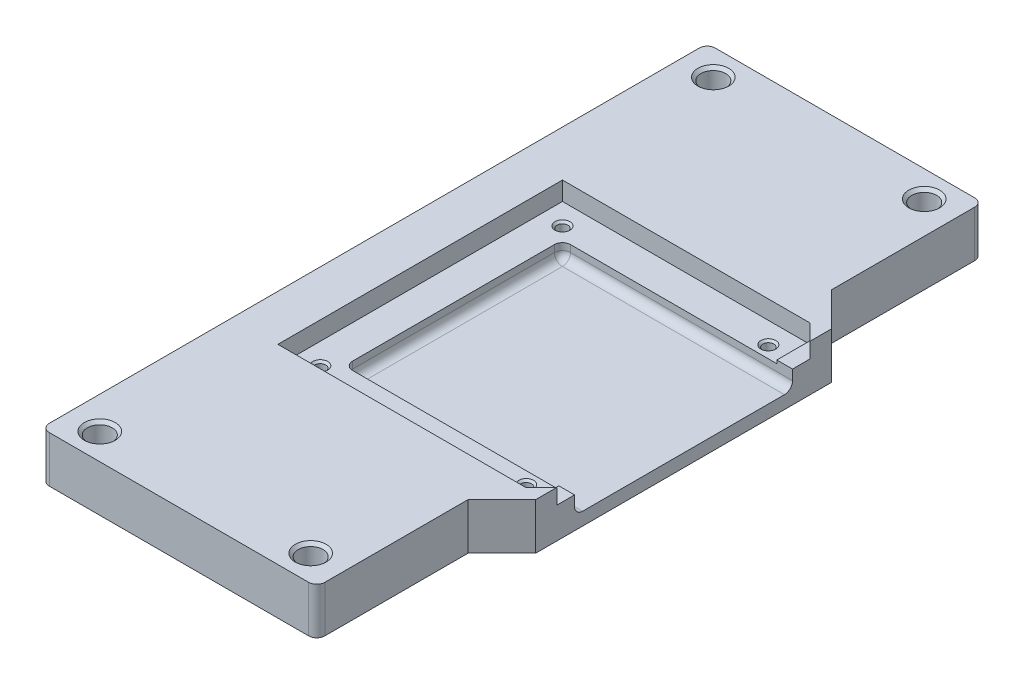
SolidWorks part; units mm, degrees
ref_plane "Front Plane" through (0, 0, 0) normal (0, 0, 1) x (1, 0, 0)
ref_plane "Top Plane" through (0, 0, 0) normal (0, 1, 0) x (1, 0, 0)
ref_plane "Right Plane" through (0, 0, 0) normal (1, 0, 0) x (0, 0, -1)
sketch "Sketch1" plane through (0, 0, 0) normal (0, 1, 0) x (1, 0, 0)
  line L0 (0, -67.5) -> (0, 67.5) construction
  line L1 (34.125, 67.5) -> (-34.125, 67.5) construction
  line L2 (-34.125, 67.5) -> (-34.125, -67.5)
  line L3 (-34.125, 0) -> (34.125, 0) construction
  line L4 (-34.125, 67.5) -> (-34.125, 80.5)
  line L5 (-32.125, 82.5) -> (32.125, 82.5)
  line L6 (0, 82.5) -> (0, 67.5) construction
  line L7 (34.125, 67.5) -> (34.125, 80.5)
  line L8 (34.125, 67.5) -> (34.125, -67.5)
  line L9 (0, -82.5) -> (0, -67.5) construction
  line L10 (34.125, -67.5) -> (-34.125, -67.5) construction
  line L11 (34.125, -67.5) -> (34.125, -80.5)
  line L12 (-32.125, -82.5) -> (32.125, -82.5)
  line L13 (-34.125, -67.5) -> (-34.125, -80.5)
  line L14 (-34.125, 70.5) -> (34.125, 70.5) construction
  circle A1 centre (-26.125, 76) radius 3.075 construction
  circle A2 centre (26.125, 76) radius 3.075 construction
  circle A5 centre (26.125, -76) radius 3.075 construction
  circle A6 centre (-26.125, -76) radius 3.075 construction
  arc A8 (-32.125, -82.5) -> (-34.125, -80.5) centre (-32.125, -80.5) cw
  arc A9 (34.125, -80.5) -> (32.125, -82.5) centre (32.125, -80.5) cw
  arc A10 (34.125, 80.5) -> (32.125, 82.5) centre (32.125, 80.5) ccw
  arc A11 (-34.125, 80.5) -> (-32.125, 82.5) centre (-32.125, 80.5) cw
  point P24 (0, 0)
  point P36 (-34.125, -82.5)
  point P39 (34.125, -82.5)
  point P42 (34.125, 82.5)
  point P45 (-34.125, 82.5)
  dimension "D10" = 2
  dimension "D3" = 6.15
  dimension "D1" = 34.125
  dimension "D2" = 67.5
  dimension "D4" = 6.5
  dimension "D6" = 8
  dimension "D7" = 8.5
  dimension "D8" = 12
  dimension "D9" = 3
  dimension "D11" = 82.5
extrude "Boss-Extrude1" add sketch "Sketch1" along normal blind 11.5
sketch "Sketch3" plane through (0, 11.5, 0) normal (0, 1, 0) x (1, 0, 0)
  line L0 (0, 0) -> (-34.125, 0) construction
  line L1 (-34.125, 80.5) -> (-34.125, -80.5) construction
  line L2 (0, 0) -> (0, 82.5) construction
  line L3 (32.125, 82.5) -> (-32.125, 82.5) construction
  line L4 (3.96, -16.3) -> (3.96, 16.3)
  line L5 (-2.46, -17.8) -> (2.46, -17.8)
  line L6 (-3.96, 16.3) -> (-3.96, -16.3)
  line L7 (2.46, 17.8) -> (-2.46, 17.8)
  line L8 (0, 17.8) -> (0, -17.8) construction
  line L9 (13.25, 0) -> (0, 0) construction
  line L10 (16.15, 10.025) -> (10.35, 10.025)
  line L11 (16.15, 10.025) -> (16.15, -10.025)
  line L12 (16.15, -10.025) -> (10.35, -10.025)
  line L13 (10.35, 10.025) -> (10.35, -10.025)
  line L14 (16.15, 10.025) -> (10.35, -10.025) construction
  line L15 (16.15, -10.025) -> (10.35, 10.025) construction
  line L16 (13.25, 0) -> (13.25, 10.025) construction
  line L17 (-16.15, 10.025) -> (-16.15, -10.025)
  line L18 (-16.15, -10.025) -> (-10.35, -10.025)
  line L23 (-16.15, 10.025) -> (-10.35, 10.025)
  line L24 (-10.35, 10.025) -> (-10.35, -10.025)
  arc A0 (-2.46, 17.8) -> (-3.96, 16.3) centre (-2.46, 16.3) ccw
  arc A1 (3.96, 16.3) -> (2.46, 17.8) centre (2.46, 16.3) ccw
  arc A2 (2.46, -17.8) -> (3.96, -16.3) centre (2.46, -16.3) ccw
  arc A3 (-3.96, -16.3) -> (-2.46, -17.8) centre (-2.46, -16.3) ccw
  point P9 (0, 0)
  point P23 (0, 0)
  dimension "D2" = 1.5
  dimension "D1" = 35.6
  dimension "D3" = 7.92
  dimension "D4" = 20.05
  dimension "D5" = 5.8
  dimension "D6" = 13.25
sketch "Sketch4" plane through (0, 11.5, 0) normal (0, 1, 0) x (1, 0, 0)
  circle A0 centre (-26.125, -76) radius 3.075 construction
  circle A1 centre (26.125, -76) radius 3.075 construction
  circle A2 centre (26.125, 76) radius 3.075 construction
  circle A5 centre (-26.125, 76) radius 3.075 construction
  circle A8 centre (-26.125, -76) radius 3.075
  circle A9 centre (26.125, -76) radius 3.075
  circle A10 centre (26.125, 76) radius 3.075
  circle A13 centre (-26.125, 76) radius 3.075
extrude "Cut-Extrude1" cut sketch "Sketch4" against normal blind 6
sketch "Sketch27" plane through (0, 11.5, 0) normal (0, 1, 0) x (1, 0, 0)
  line L0 (38.5, 35) -> (-22.5, 35) construction
  line L1 (34.125, 45) -> (42.5, 36.625)
  line L2 (-22.5, 35) -> (-22.5, -35) construction
  line L3 (-22.5, 0) -> (0, 0) construction
  line L4 (38.5, -35) -> (38.5, 35) construction
  line L5 (38.5, -35) -> (-22.5, -35) construction
  line L7 (0, 0) -> (38.5, 0) construction
  line L8 (34.125, -80.5) -> (34.125, 80.5) construction
  line L9 (42.5, 36.625) -> (42.5, -36.625)
  line L10 (42.5, 0) -> (38.5, 0) construction
  line L11 (34.125, 45) -> (34.125, -45)
  line L12 (34.125, 0) -> (42.5, 0) construction
  line L13 (34.125, -45) -> (42.5, -36.625)
  circle A0 centre (-17.5, 30) radius 1.6 construction
  circle A1 centre (33.5, 30) radius 1.6 construction
  circle A2 centre (33.5, -30) radius 1.6 construction
  circle A3 centre (-17.5, -30) radius 1.6 construction
  dimension "D8" = 3.2
  dimension "D1" = 22.5
  dimension "D2" = 61
  dimension "D3" = 35
  dimension "D4" = 5
  dimension "D5" = 5
  dimension "D6" = 5
  dimension "D7" = 5
  dimension "D9" = 45
  dimension "D10" = 4
  dimension "D11" = 10
extrude "Boss-Extrude3" add sketch "Sketch27" against normal up to surface (11.5 mm away) up to face at (0, 0, 0)
sketch "Sketch21" plane through (0, 11.5, 0) normal (0, 1, 0) x (1, 0, 0)
  line L0 (38.5, 35) -> (-22.5, 35) construction
  line L1 (38.5, 35) -> (42.5, 31) construction
  line L2 (-22.5, 35) -> (-22.5, -35) construction
  line L3 (-22.5, 0) -> (0, 0) construction
  line L5 (38.5, -35) -> (38.5, 35) construction
  line L6 (38.5, -35) -> (-22.5, -35) construction
  line L7 (42.5, 31) -> (42.5, 31.3536) construction
  line L10 (0, 0) -> (38.5, 0) construction
  line L11 (42.5, 31.3536) -> (42.5, -31.3536)
  line L14 (38.6036, 35.25) -> (42.5, 31.3536)
  line L15 (38.6036, 35.25) -> (-22.75, 35.25)
  line L16 (-22.75, 35.25) -> (-22.75, -35.25)
  line L17 (38.6036, -35.25) -> (-22.75, -35.25)
  line L22 (41.1909, -32.6626) -> (40.4837, -33.8199) construction
  line L23 (42.5, 31.3536) -> (43.8534, 32.707) construction
  line L24 (42.5, -31) -> (40.697, -33.9503) construction
  line L25 (42.5, 31) -> (44.0302, 32.5302) construction
  line L26 (38.6036, -35.25) -> (41.1909, -32.6626) construction
  line L27 (38.5, -35) -> (42.5, -31) construction
  line L29 (42.5, 0) -> (38.5, 0) construction
  line L30 (42.5, -36.625) -> (42.5, 36.625) construction
  line L31 (38.6036, -35.25) -> (42.5, -31.3536)
  circle A0 centre (-17.5, 30) radius 1.6 construction
  circle A1 centre (33.5, 30) radius 1.6 construction
  circle A2 centre (33.5, -30) radius 1.6 construction
  circle A3 centre (-17.5, -30) radius 1.6 construction
  point P2 (-123.1318, 54.1866)
  point P19 (42.5, 0)
  dimension "D8" = 3.2
  dimension "D1" = 22.5
  dimension "D2" = 61
  dimension "D3" = 35
  dimension "D4" = 5
  dimension "D5" = 5
  dimension "D6" = 5
  dimension "D7" = 5
  dimension "D9" = 45
  dimension "D10" = 4
  dimension "D11" = 0.25
extrude "Cut-Extrude6" cut sketch "Sketch21" against normal blind 4.6
sketch "Sketch24" plane through (0, 6.9, 0) normal (0, 1, 0) x (1, 0, 0)
  line L0 (42.5, 27) -> (-14.5, 27)
  line L1 (42.5, -31.3536) -> (42.5, 31.3536) construction
  line L2 (-14.5, 27) -> (-14.5, -27)
  line L3 (-14.5, -27) -> (42.5, -27)
  line L4 (42.5, -27) -> (42.5, 27)
  line L8 (38.5, 35) -> (-22.5, 35) construction
  line L10 (-22.5, 35) -> (-22.5, -35) construction
  line L11 (38.5, -35) -> (-22.5, -35) construction
  point P2 (0, 0)
  point P3 (42.5, -27)
  dimension "D1" = 8
  dimension "D2" = 8
  dimension "D3" = 8
extrude "Cut-Extrude3" cut sketch "Sketch24" against normal blind 3.7 and the other way through all
sketch "Sketch25" plane through (0, 6.9, 0) normal (0, 1, 0) x (1, 0, 0)
  circle A0 centre (33.5, 30) radius 1.35
  circle A1 centre (-17.5, 30) radius 1.35
  circle A2 centre (33.5, -30) radius 1.35
  circle A3 centre (-17.5, -30) radius 1.35
  dimension "D1" = 2.7
extrude "Cut-Extrude4" cut sketch "Sketch25" against normal blind 5
chamfer "Chamfer4" distance 0.5 angle 45 4 edges at (-17.5, 6.9, 31.35) (33.5, 6.9, 31.35) (33.5, 6.9, -28.65) (-17.5, 6.9, -28.65)
fillet "Fillet1" radius 2 5 edges at (14, 3.2, 27) (-14.5, 5.05, 27) (-14.5, 5.05, -27) (-14.5, 3.2, 0) (14, 3.2, -27)
sketch "Sketch26" plane through (0, 6.9, 0) normal (0, 1, 0) x (1, 0, 0)
  line L0 (0, 0) -> (34.125, 0) construction
  line L1 (34.125, -25) -> (34.125, 25) construction
  line L2 (38.6036, 35.25) -> (38.6036, 27)
  line L3 (42.5, 27) -> (-12.5, 27) construction
  line L4 (38.6036, 27) -> (42.5, 27)
  line L5 (42.5, 27) -> (42.5, 31.3536)
  line L7 (42.5, 31.3536) -> (38.6036, 35.25)
  line L8 (42.5, -31.3536) -> (38.6036, -35.25)
  line L11 (38.6036, -27) -> (42.5, -27)
  line L12 (38.6036, -35.25) -> (38.6036, -27)
  line L13 (42.5, 27) -> (42.5, 31.3536) construction
  line L14 (42.5, -31.3536) -> (42.5, -27)
extrude "Boss-Extrude2" add sketch "Sketch26" along normal blind 0.8
chamfer "Chamfer5" distance 0.75 angle 45 4 edges at (-26.125, 11.5, 79.075) (26.125, 11.5, 79.075) (26.125, 11.5, -72.925) (-26.125, 11.5, -72.925)
equation "\"D5@Sketch21\"=\"D4@Sketch21\""
equation "\"D6@Sketch21\"=\"D4@Sketch21\""
equation "\"D7@Sketch21\"=\"D4@Sketch21\""
equation "\"D2@Sketch24\"=\"D1@Sketch24\""
equation "\"D3@Sketch24\"=\"D1@Sketch24\""
